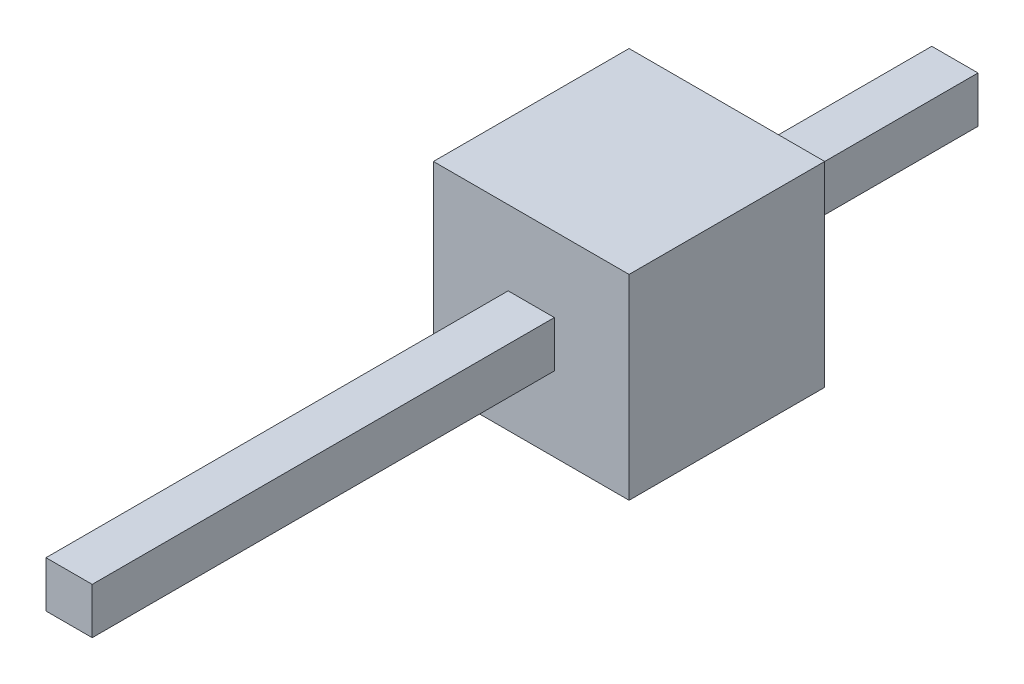
SolidWorks part; units mm, degrees
ref_plane "Alzado" through (0, 0, 0) normal (0, 0, 1) x (1, 0, 0)
ref_plane "Planta" through (0, 0, 0) normal (0, 1, 0) x (1, 0, 0)
ref_plane "Vista lateral" through (0, 0, 0) normal (1, 0, 0) x (0, 0, -1)
sketch "Croquis1" plane through (0, 0, 0) normal (0, 0, 1) x (1, 0, 0)
  line L1 (1.27, -1.27) -> (-1.27, -1.27)
  line L2 (1.27, -1.27) -> (1.27, 1.27)
  line L3 (1.27, 1.27) -> (-1.27, 1.27)
  line L4 (-1.27, -1.27) -> (-1.27, 1.27)
  line L5 (1.27, -1.27) -> (-1.27, 1.27) construction
  line L6 (1.27, 1.27) -> (-1.27, -1.27) construction
  line L7 (0.3, -0.3) -> (-0.3, -0.3)
  line L8 (0.3, -0.3) -> (0.3, 0.3)
  line L9 (0.3, 0.3) -> (-0.3, 0.3)
  line L10 (-0.3, -0.3) -> (-0.3, 0.3)
  line L11 (0.3, -0.3) -> (-0.3, 0.3) construction
  line L12 (0.3, 0.3) -> (-0.3, -0.3) construction
  point P0 (0, 0)
  point P6 (0, 0)
  dimension "D1" = 2.54
  dimension "D2" = 0.6
extrude "Saliente-Extruir1" add sketch "Croquis1" along normal blind 2.54
sketch "Croquis2" plane through (0, 0, 2.54) normal (0, 0, 1) x (1, 0, 0)
  line L0 (-0.3, 0.3) -> (-0.3, -0.3) construction
  line L1 (-0.3, -0.3) -> (0.3, -0.3) construction
  line L2 (0.3, -0.3) -> (0.3, 0.3) construction
  line L3 (0.3, 0.3) -> (-0.3, 0.3) construction
  line L4 (-0.3, 0.3) -> (-0.3, -0.3)
  line L5 (-0.3, -0.3) -> (0.3, -0.3)
  line L6 (0.3, -0.3) -> (0.3, 0.3)
  line L7 (0.3, 0.3) -> (-0.3, 0.3)
extrude "Saliente-Extruir2" add sketch "Croquis2" along normal blind 6 and the other way blind 5.5
